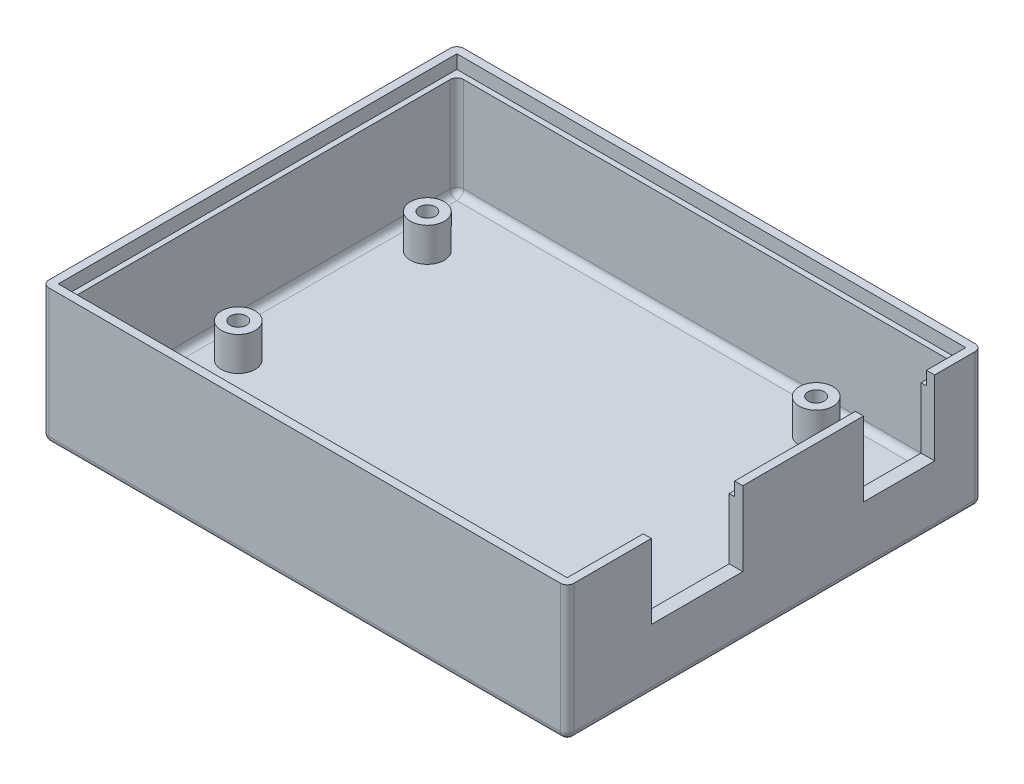
SolidWorks part; units mm, degrees
ref_plane "Front" through (0, 0, 0) normal (0, 0, 1) x (1, 0, 0)
ref_plane "Top" through (0, 0, 0) normal (0, 1, 0) x (1, 0, 0)
ref_plane "Right" through (0, 0, 0) normal (1, 0, 0) x (0, 0, -1)
sketch "Sketch1" plane through (0, 0, 0) normal (0, 1, 0) x (1, 0, 0)
  line L0 (35.8, -27.65) -> (-35.8, 27.65) construction
  line L1 (35.8, -27.65) -> (-35.8, -27.65) construction
  line L2 (35.8, -27.65) -> (35.8, 27.65) construction
  line L3 (35.8, 27.65) -> (-35.8, 27.65) construction
  line L4 (-35.8, -27.65) -> (-35.8, 27.65) construction
  line L5 (-35.8, 27.65) -> (-35.8, -27.65) construction
  line L6 (-35.8, -27.65) -> (35.8, 27.65) construction
  circle A0 centre (-32.6, 19.09) radius 2.5
  circle A1 centre (-32.6, -8.85) radius 2.5
  circle A2 centre (19.8, 24.15) radius 2.5
  circle A3 centre (18.5, -24.05) radius 2.5
  point P8 (0, 0)
  dimension "D5" = 5
  dimension "D6" = 5
  dimension "D7" = 5
  dimension "D8" = 5
  dimension "D3" = 51.1
  dimension "D13" = 27.94
  dimension "D2" = 71.6
  dimension "D9" = 55.3
  dimension "D10" = 17.3
  dimension "D14" = 3.5
  dimension "D4" = 8.56
  dimension "D12" = 48.2
  dimension "D11" = 16
extrude "Boss-Extrude1" add sketch "Sketch1" against normal blind 5
sketch "Sketch3" plane through (0, -5, 0) normal (0, -1, 0) x (1, 0, 0)
  line L0 (-39.8, -30.65) -> (37.8, 30.65) construction
  line L1 (-39.8, 30.65) -> (37.8, 30.65)
  line L2 (-39.8, 30.65) -> (-39.8, -30.65)
  line L3 (-39.8, -30.65) -> (37.8, -30.65)
  line L4 (37.8, 30.65) -> (37.8, -30.65)
  line L5 (-39.8, 30.65) -> (37.8, -30.65) construction
  line L6 (35.8, 27.65) -> (-35.8, -27.65) construction
  line L7 (35.8, 27.65) -> (-35.8, 27.65) construction
  line L8 (35.8, 27.65) -> (35.8, -27.65) construction
  line L9 (35.8, -27.65) -> (-35.8, -27.65) construction
  line L10 (-35.8, 27.65) -> (-35.8, -27.65) construction
  line L11 (-35.8, -27.65) -> (-35.8, 27.65) construction
  line L12 (-35.8, 27.65) -> (35.8, -27.65) construction
  point P0 (0, 0)
  point P5 (-1, 0)
  dimension "D3" = 71.6
  dimension "D4" = 55.3
  dimension "D1" = 77.6
  dimension "D2" = 61.3
  dimension "D5" = 1
extrude "Boss-Extrude2" add sketch "Sketch3" along normal blind 3
sketch "Sketch4" plane through (0, -5, 0) normal (0, 1, 0) x (1, 0, 0)
  line L0 (-39.8, -30.65) -> (-39.8, 30.65) construction
  line L1 (-39.8, -30.65) -> (37.8, -30.65)
  line L2 (-39.8, -30.65) -> (-39.8, 30.65)
  line L3 (-39.8, 30.65) -> (37.8, 30.65)
  line L4 (37.8, -30.65) -> (37.8, 30.65)
  line L5 (-37.8, -28.65) -> (35.8, -28.65)
  line L6 (-37.8, -28.65) -> (-37.8, 28.65)
  line L7 (-37.8, 28.65) -> (35.8, 28.65)
  line L8 (35.8, -28.65) -> (35.8, 28.65)
  line L9 (37.8, -30.65) -> (-39.8, -30.65) construction
  dimension "D1" = 2
  dimension "D2" = 2
  dimension "D3" = 2
  dimension "D4" = 2
extrude "Boss-Extrude3" add sketch "Sketch4" along normal blind 17
sketch "Sketch5" plane through (37.8, 0, 0) normal (1, 0, 0) x (0, 0, -1)
  line L1 (-18.2, 12) -> (-4.7, 12)
  line L2 (-18.2, 12) -> (-18.2, 1)
  line L3 (-18.2, 1) -> (-4.7, 1)
  line L4 (-4.7, 12) -> (-4.7, 1)
  line L6 (-24.05, -5) -> (-24.05, 0) construction
  line L7 (24.15, -5) -> (24.15, 0) construction
  line L8 (13.15, 12) -> (23.65, 12)
  line L9 (13.15, 12) -> (13.15, 1)
  line L10 (13.15, 1) -> (23.65, 1)
  line L11 (23.65, 12) -> (23.65, 1)
  line L13 (-21.55, 0) -> (-26.55, 0) construction
  line L14 (-30.65, 12) -> (30.65, 12) construction
  dimension "D2" = 13.5
  dimension "D3" = 1
  dimension "D4" = 5.85
  dimension "D5" = 10.5
  dimension "D7" = 0.5
extrude "Cut-Extrude2" cut sketch "Sketch5" against normal up to next
fillet "Fillet1" radius 1 8 edges at (35.8, 3.5, -28.65) (-1, -5, -28.65) (35.8, 3.5, 28.65) (-1, -5, 28.65) (-37.8, 3.5, 28.65) (-37.8, 3.5, -28.65) (-37.8, -5, 0) (37.8, -8, 0)
fillet "Fillet2" radius 1 9 edges at (-1.5, -8, -30.65) (-39.8, -8, 0) (-1.5, -8, 30.65) (37.8, 2.5, 30.65) (37.8, 2.5, -30.65) (-39.8, 2, -30.65) (-39.8, 2, 30.65) (37.5071, -7.7071, 30.65) (37.5071, -7.7071, -30.65)
sketch "Sketch7" plane through (0, 12, 0) normal (0, 1, 0) x (1, 0, 0)
  line L0 (-38.8, -30.65) -> (36.8, -30.65) construction
  line L1 (-38.6, -29.45) -> (36.6, -29.45)
  line L2 (-38.6, -29.45) -> (-38.6, 29.45)
  line L3 (-38.6, 29.45) -> (36.6, 29.45)
  line L4 (36.6, -29.45) -> (36.6, 29.45)
  line L5 (-39.8, 29.65) -> (-39.8, -29.65) construction
  line L6 (36.8, 30.65) -> (-38.8, 30.65) construction
  line L7 (37.8, -4.7) -> (37.8, 13.15) construction
  point P12 (37.8, 4.225)
  dimension "D1" = 1.2
  dimension "D2" = 1.2
  dimension "D3" = 1.2
  dimension "D4" = 1.2
extrude "Cut-Extrude3" cut sketch "Sketch7" against normal blind 2
sketch "Sketch2" plane through (0, 0, 0) normal (0, 1, 0) x (1, 0, 0)
  circle A0 centre (-32.6, -8.85) radius 1
  circle A1 centre (-32.6, 19.09) radius 1
  circle A2 centre (19.8, 24.15) radius 1
  circle A3 centre (18.5, -24.05) radius 1
  circle A4 centre (-32.6, -8.85) radius 2.5 construction
  circle A5 centre (-32.6, 19.09) radius 2.5 construction
  circle A6 centre (19.8, 24.15) radius 2.5 construction
  circle A7 centre (18.5, -24.05) radius 2.5 construction
  dimension "D1" = 2
  dimension "D2" = 2
  dimension "D3" = 2
  dimension "D4" = 2
extrude "Cut-Extrude1" cut sketch "Sketch2" against normal through all
hole_wizard "CSK for M2 Flat Head Machine Screw1" positions "Sketch10" profile "Sketch11" countersink size "M2" standard "ANSI Metric" end condition through all
sketch "Sketch10" plane through (0, -8, 0) normal (0, -1, 0) x (-1, 0, 0)
  point P0 (32.6, 19.09)
  point P3 (32.6, -8.85)
  point P6 (-18.5, -24.05)
  point P9 (-19.8, 24.15)
sketch "Sketch11" plane through (-32.6, -8, -19.09) normal (1, 0, 0) x (0, 0, -1)
  line L0 (0, 0) -> (0, 20)
  line L1 (0, 20) -> (1.2, 20)
  line L2 (1.2, 20) -> (1.2, 1)
  line L3 (1.2, 1) -> (2.2, 0)
  line L5 (2.2, 0) -> (0, 0)
  line L6 (-1.2, 1) -> (-2.2, 0) construction
  line L11 (0, -6.35) -> (0, 107.95) construction
  dimension "Thru Hole Dia." = 2.4
  dimension "Thru Hole Depth" = 20
  dimension "Near C'Sink Dia." = 4.4
  dimension "Near C'Sink Angle" = 90
equation "\"D6@Sketch1\"=\"D5@Sketch1\""
equation "\"D7@Sketch1\"=\"D5@Sketch1\""
equation "\"D8@Sketch1\"=\"D5@Sketch1\""
equation "\"D2@Sketch2\"=\"D1@Sketch2\""
equation "\"D3@Sketch2\"=\"D1@Sketch2\""
equation "\"D4@Sketch2\"=\"D1@Sketch2\""
equation "\"D2@Sketch4\"=\"D1@Sketch4\""
equation "\"D3@Sketch4\"=\"D1@Sketch4\""
equation "\"D4@Sketch4\"=\"D1@Sketch4\""
equation "\"D1@Sketch3\"=\"D3@Sketch3\"+6"
equation "\"D2@Sketch3\"=\"D4@Sketch3\"+6"
equation "\"D3@Sketch7\"=\"D1@Sketch7\""
equation "\"D2@Sketch7\"=\"D1@Sketch7\""
equation "\"D4@Sketch7\"=\"D1@Sketch7\""
